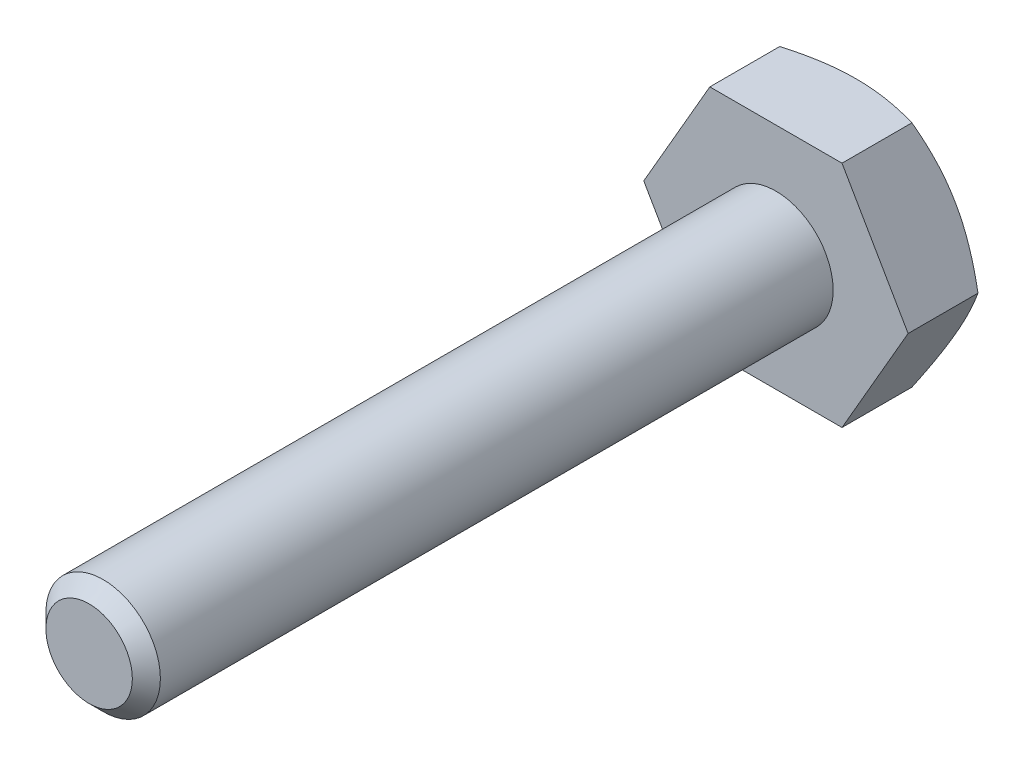
SolidWorks part; units mm, degrees
material "Plain Carbon Steel"
ref_plane "Front Plane" through (0, 0, 0) normal (0, 0, 1) x (1, 0, 0)
ref_plane "Top Plane" through (0, 0, 0) normal (0, 1, 0) x (1, 0, 0)
ref_plane "Right Plane" through (0, 0, 0) normal (1, 0, 0) x (0, 0, -1)
sketch "Sketch1" plane through (0, 0, 0) normal (0, 0, 1) x (1, 0, 0)
  line L1 (2.3094, 0) -> (1.1547, 2)
  line L2 (1.1547, 2) -> (-1.1547, 2)
  line L3 (-1.1547, 2) -> (-2.3094, 0)
  line L4 (-2.3094, 0) -> (-1.1547, -2)
  line L5 (-1.1547, -2) -> (1.1547, -2)
  line L6 (1.1547, -2) -> (2.3094, 0)
  circle A0 centre (0, 0) radius 2 construction
  dimension "D1" = 4
extrude "Extrude1" add sketch "Sketch1" along normal blind 1.4
sketch "Sketch2" plane through (0, 0, 1.4) normal (0, 0, 1) x (1, 0, 0)
  circle A0 centre (0, 0) radius 1
  dimension "D1" = 2
extrude "Extrude2" add sketch "Sketch2" along normal blind 12
cosmetic thread "Cosmetic Thread1" parameters "D2"=1.51
sketch "Sketch3" plane through (0, 0, 0) normal (1, 0, 0) x (0, 0, -1)
  line L0 (0, 2) -> (0, 102)
  line L1 (0, 102) -> (-57.735, 102)
  line L2 (-57.735, 102) -> (0, 2)
  line L3 (0, 0) -> (11.4679, 0) construction
  dimension "D1" = 30
  dimension "D2" = 100
revolve "Cut-Revolve1" cut sketch "Sketch3" angle 360 about L3
chamfer "Chamfer1" distance 0.245 angle 45 1 edges at (1, 0, 13.4)
